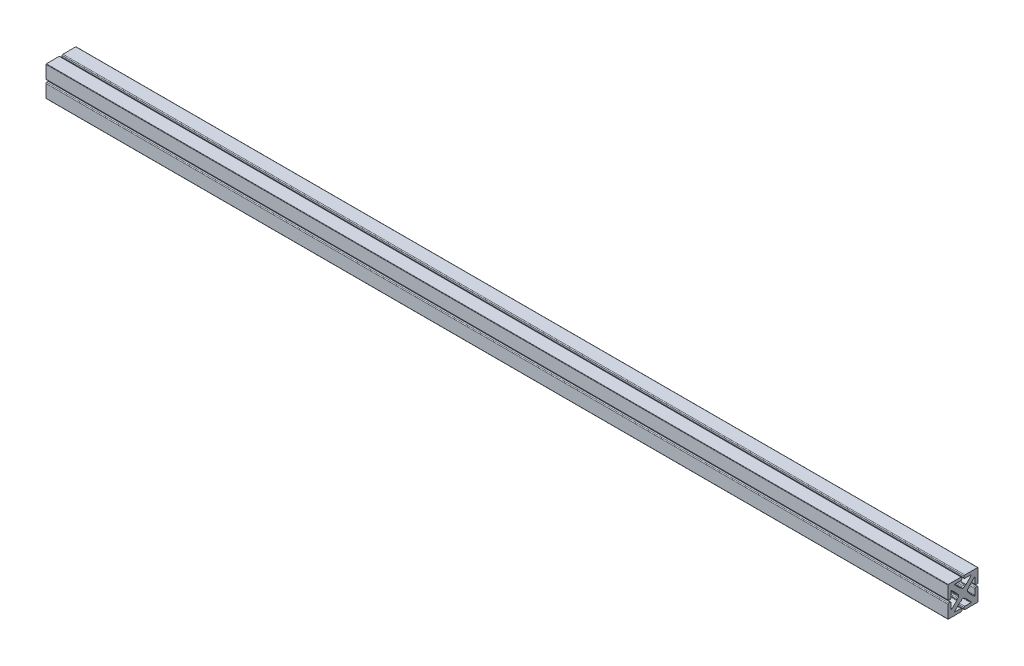
SolidWorks part; units mm, degrees
material "1060 Alloy"
ref_plane "Front Plane" through (0, 0, 0) normal (0, 0, 1) x (1, 0, 0)
ref_plane "Top Plane" through (0, 0, 0) normal (0, 1, 0) x (1, 0, 0)
ref_plane "Right Plane" through (0, 0, 0) normal (1, 0, 0) x (0, 0, -1)
sketch "Sketch1" plane through (0, 0, 0) normal (1, 0, 0) x (0, 0, -1)
  line L0 (0, 0) -> (0, 1.4986) construction
  line L1 (-0.2413, 1.4986) -> (0.2413, 1.4986)
  line L2 (5.0038, 0.635) -> (5.0038, 4.8768)
  line L3 (0.7493, 2.0066) -> (0.8825, 2.0066)
  line L4 (1.0655, 2.0845) -> (2.7141, 3.7982)
  line L5 (2.6226, 4.0132) -> (0.635, 4.0132)
  line L6 (0.381, 4.2672) -> (0.381, 4.7498)
  line L7 (0.635, 5.0038) -> (4.8768, 5.0038)
  line L8 (5.0038, 5.0038) -> (0, 0) construction
  line L9 (0, 0) -> (8.6271, 0) construction
  line L10 (0, 0) -> (0, 5.0038) construction
  line L11 (4.2672, 0.381) -> (4.7498, 0.381)
  line L12 (4.0132, 2.6226) -> (4.0132, 0.635)
  line L13 (2.0845, 1.0655) -> (3.7982, 2.7141)
  line L14 (2.0066, 0.7493) -> (2.0066, 0.8825)
  line L15 (1.4986, -0.2413) -> (1.4986, 0.2413)
  line L16 (0, 0) -> (1.4986, 0) construction
  line L17 (-0.2413, -1.4986) -> (0.2413, -1.4986)
  line L18 (0.7493, -2.0066) -> (0.8825, -2.0066)
  line L19 (1.0655, -2.0845) -> (2.7141, -3.7982)
  line L20 (2.6226, -4.0132) -> (0.635, -4.0132)
  line L21 (0.381, -4.2672) -> (0.381, -4.7498)
  line L22 (0.635, -5.0038) -> (4.8768, -5.0038)
  line L23 (5.0038, -0.635) -> (5.0038, -4.8768)
  line L24 (4.2672, -0.381) -> (4.7498, -0.381)
  line L25 (4.0132, -2.6226) -> (4.0132, -0.635)
  line L26 (2.0845, -1.0655) -> (3.7982, -2.7141)
  line L27 (2.0066, -0.7493) -> (2.0066, -0.8825)
  line L28 (-0.7493, 2.0066) -> (-0.8825, 2.0066)
  line L29 (-1.0655, 2.0845) -> (-2.7141, 3.7982)
  line L30 (-2.6226, 4.0132) -> (-0.635, 4.0132)
  line L31 (-0.381, 4.2672) -> (-0.381, 4.7498)
  line L32 (-0.635, 5.0038) -> (-4.8768, 5.0038)
  line L33 (-5.0038, 0.635) -> (-5.0038, 4.8768)
  line L34 (-4.2672, 0.381) -> (-4.7498, 0.381)
  line L35 (-4.0132, 2.6226) -> (-4.0132, 0.635)
  line L36 (-2.0845, 1.0655) -> (-3.7982, 2.7141)
  line L37 (-2.0066, 0.7493) -> (-2.0066, 0.8825)
  line L38 (-1.4986, -0.2413) -> (-1.4986, 0.2413)
  line L39 (-2.0066, -0.7493) -> (-2.0066, -0.8825)
  line L40 (-2.0845, -1.0655) -> (-3.7982, -2.7141)
  line L41 (-4.0132, -2.6226) -> (-4.0132, -0.635)
  line L42 (-4.2672, -0.381) -> (-4.7498, -0.381)
  line L43 (-5.0038, -0.635) -> (-5.0038, -4.8768)
  line L44 (-0.635, -5.0038) -> (-4.8768, -5.0038)
  line L45 (-0.381, -4.2672) -> (-0.381, -4.7498)
  line L46 (-2.6226, -4.0132) -> (-0.635, -4.0132)
  line L47 (-1.0655, -2.0845) -> (-2.7141, -3.7982)
  line L48 (-0.7493, -2.0066) -> (-0.8825, -2.0066)
  arc A0 (2.7141, 3.7982) -> (2.6226, 4.0132) centre (2.6226, 3.8862) ccw
  arc A1 (0.4953, 1.7526) -> (0.7493, 2.0066) centre (0.7493, 1.7526) cw
  arc A2 (0.8825, 2.0066) -> (1.0655, 2.0845) centre (0.8825, 2.2606) ccw
  arc A3 (0.635, 4.0132) -> (0.381, 4.2672) centre (0.635, 4.2672) cw
  arc A4 (0.381, 4.7498) -> (0.635, 5.0038) centre (0.635, 4.7498) cw
  arc A5 (0.2413, 1.4986) -> (0.4953, 1.7526) centre (0.2413, 1.7526) ccw
  arc A6 (4.7498, 0.381) -> (5.0038, 0.635) centre (4.7498, 0.635) ccw
  arc A7 (4.0132, 0.635) -> (4.2672, 0.381) centre (4.2672, 0.635) ccw
  arc A8 (3.7982, 2.7141) -> (4.0132, 2.6226) centre (3.8862, 2.6226) cw
  arc A9 (2.0066, 0.8825) -> (2.0845, 1.0655) centre (2.2606, 0.8825) cw
  arc A10 (1.7526, 0.4953) -> (2.0066, 0.7493) centre (1.7526, 0.7493) ccw
  arc A11 (1.4986, 0.2413) -> (1.7526, 0.4953) centre (1.7526, 0.2413) cw
  arc A12 (0.2413, -1.4986) -> (0.4953, -1.7526) centre (0.2413, -1.7526) cw
  arc A13 (0.4953, -1.7526) -> (0.7493, -2.0066) centre (0.7493, -1.7526) ccw
  arc A14 (0.8825, -2.0066) -> (1.0655, -2.0845) centre (0.8825, -2.2606) cw
  arc A15 (2.7141, -3.7982) -> (2.6226, -4.0132) centre (2.6226, -3.8862) cw
  arc A16 (0.635, -4.0132) -> (0.381, -4.2672) centre (0.635, -4.2672) ccw
  arc A17 (0.381, -4.7498) -> (0.635, -5.0038) centre (0.635, -4.7498) ccw
  arc A18 (4.7498, -0.381) -> (5.0038, -0.635) centre (4.7498, -0.635) cw
  arc A19 (4.0132, -0.635) -> (4.2672, -0.381) centre (4.2672, -0.635) cw
  arc A20 (3.7982, -2.7141) -> (4.0132, -2.6226) centre (3.8862, -2.6226) ccw
  arc A21 (2.0066, -0.8825) -> (2.0845, -1.0655) centre (2.2606, -0.8825) ccw
  arc A22 (1.7526, -0.4953) -> (2.0066, -0.7493) centre (1.7526, -0.7493) cw
  arc A23 (1.4986, -0.2413) -> (1.7526, -0.4953) centre (1.7526, -0.2413) ccw
  arc A24 (-0.2413, 1.4986) -> (-0.4953, 1.7526) centre (-0.2413, 1.7526) cw
  arc A25 (-0.4953, 1.7526) -> (-0.7493, 2.0066) centre (-0.7493, 1.7526) ccw
  arc A26 (-0.8825, 2.0066) -> (-1.0655, 2.0845) centre (-0.8825, 2.2606) cw
  arc A27 (-2.7141, 3.7982) -> (-2.6226, 4.0132) centre (-2.6226, 3.8862) cw
  arc A28 (-0.635, 4.0132) -> (-0.381, 4.2672) centre (-0.635, 4.2672) ccw
  arc A29 (-0.381, 4.7498) -> (-0.635, 5.0038) centre (-0.635, 4.7498) ccw
  arc A30 (-4.7498, 0.381) -> (-5.0038, 0.635) centre (-4.7498, 0.635) cw
  arc A31 (-4.0132, 0.635) -> (-4.2672, 0.381) centre (-4.2672, 0.635) cw
  arc A32 (-3.7982, 2.7141) -> (-4.0132, 2.6226) centre (-3.8862, 2.6226) ccw
  arc A33 (-2.0066, 0.8825) -> (-2.0845, 1.0655) centre (-2.2606, 0.8825) ccw
  arc A34 (-1.7526, 0.4953) -> (-2.0066, 0.7493) centre (-1.7526, 0.7493) cw
  arc A35 (-1.4986, 0.2413) -> (-1.7526, 0.4953) centre (-1.7526, 0.2413) ccw
  arc A36 (-1.4986, -0.2413) -> (-1.7526, -0.4953) centre (-1.7526, -0.2413) cw
  arc A37 (-1.7526, -0.4953) -> (-2.0066, -0.7493) centre (-1.7526, -0.7493) ccw
  arc A38 (-2.0066, -0.8825) -> (-2.0845, -1.0655) centre (-2.2606, -0.8825) cw
  arc A39 (-3.7982, -2.7141) -> (-4.0132, -2.6226) centre (-3.8862, -2.6226) cw
  arc A40 (-4.0132, -0.635) -> (-4.2672, -0.381) centre (-4.2672, -0.635) ccw
  arc A41 (-4.7498, -0.381) -> (-5.0038, -0.635) centre (-4.7498, -0.635) ccw
  arc A42 (-0.381, -4.7498) -> (-0.635, -5.0038) centre (-0.635, -4.7498) cw
  arc A43 (-0.635, -4.0132) -> (-0.381, -4.2672) centre (-0.635, -4.2672) cw
  arc A44 (-2.7141, -3.7982) -> (-2.6226, -4.0132) centre (-2.6226, -3.8862) ccw
  arc A45 (-0.8825, -2.0066) -> (-1.0655, -2.0845) centre (-0.8825, -2.2606) ccw
  arc A46 (-0.4953, -1.7526) -> (-0.7493, -2.0066) centre (-0.7493, -1.7526) cw
  arc A47 (-0.2413, -1.4986) -> (-0.4953, -1.7526) centre (-0.2413, -1.7526) ccw
  arc A48 (-4.8768, 5.0038) -> (-5.0038, 4.8768) centre (-4.8768, 4.8768) ccw
  arc A49 (-5.0038, -4.8768) -> (-4.8768, -5.0038) centre (-4.8768, -4.8768) ccw
  arc A50 (4.8768, -5.0038) -> (5.0038, -4.8768) centre (4.8768, -4.8768) ccw
  arc A51 (4.8768, 5.0038) -> (5.0038, 4.8768) centre (4.8768, 4.8768) cw
  point P14 (2.921, 4.0132)
  point P19 (0.9906, 2.0066)
  point P150 (0, -1.4986)
  point P152 (-5.0038, 5.0038)
  point P155 (-5.0038, -5.0038)
  point P158 (5.0038, -5.0038)
  dimension "D10" = 0.127
  dimension "D11" = 0.254
  dimension "D2" = 0.127
  dimension "D1" = 10.0076
  dimension "D3" = 2.9972
  dimension "D4" = 0.508
  dimension "D5" = 0.762
  dimension "D6" = 0.9906
  dimension "D7" = 2.54
  dimension "D8" = 1.9812
  dimension "D9" = 0.9906
extrude "Boss-Extrude1" add sketch "Sketch1" along normal blind 2.54 contours L33 A48 L32 A29 L31 A28 L30 A27 L29 A26 L28 A25 A24 L1 A5 A1 L3 A2 L4 A0 L5 A3 L6 A4 L7 A51 L2 A6 L11 A7 L12 A8 L13 A9 L14 A10 A11 L15 A23 A22 L27 A21 L26 A20 L25 A19 L24 A18 L23 A50 L22 A17 L21 A16 L20 A15 L19 A14 L18 A13 A12 L17 A47 A46 L48 A45 L47 A44 L46 A43 L45 A42 L44 A49 L43 A41 L42 A40 L41 A39 L40 A38 L39 A37 A36 L38 A35 A34 L37 A33 L36 A32 L35 A31 L34 A30
scale "Scale1" scale about centroid uniform scaling yes scale factor 8
sketch "Sketch2" plane through (0, 0, 0) normal (1, 0, 0) x (0, 0, -1)
  line L44 (-37.9984, 3.048) -> (-34.1376, 3.048)
  line L45 (-32.1056, 5.08) -> (-32.1056, 20.9808)
  line L46 (-30.3852, 21.7129) -> (-16.676, 8.5244)
  line L47 (-16.0528, 7.06) -> (-16.0528, 5.9944)
  line L48 (-11.9888, 1.9304) -> (-11.9888, -1.9304)
  line L49 (-16.0528, -5.9944) -> (-16.0528, -7.06)
  line L50 (-16.676, -8.5244) -> (-30.3852, -21.7129)
  line L51 (-32.1056, -20.9808) -> (-32.1056, -5.08)
  line L52 (-34.1376, -3.048) -> (-37.9984, -3.048)
  line L53 (-40.0304, -5.08) -> (-40.0304, -39.0144)
  line L54 (-39.0144, -40.0304) -> (-5.08, -40.0304)
  line L55 (-3.048, -37.9984) -> (-3.048, -34.1376)
  line L56 (-5.08, -32.1056) -> (-20.9808, -32.1056)
  line L57 (-21.7129, -30.3852) -> (-8.5244, -16.676)
  line L58 (-7.06, -16.0528) -> (-5.9944, -16.0528)
  line L59 (-1.9304, -11.9888) -> (1.9304, -11.9888)
  line L60 (5.9944, -16.0528) -> (7.06, -16.0528)
  line L61 (8.5244, -16.676) -> (21.7129, -30.3852)
  line L62 (20.9808, -32.1056) -> (5.08, -32.1056)
  line L63 (3.048, -34.1376) -> (3.048, -37.9984)
  line L64 (5.08, -40.0304) -> (39.0144, -40.0304)
  line L65 (40.0304, -39.0144) -> (40.0304, -5.08)
  line L66 (37.9984, -3.048) -> (34.1376, -3.048)
  line L67 (32.1056, -5.08) -> (32.1056, -20.9808)
  line L68 (30.3852, -21.7129) -> (16.676, -8.5244)
  line L69 (16.0528, -7.06) -> (16.0528, -5.9944)
  line L70 (11.9888, -1.9304) -> (11.9888, 1.9304)
  line L71 (16.0528, 5.9944) -> (16.0528, 7.06)
  line L72 (16.676, 8.5244) -> (30.3852, 21.7129)
  line L73 (32.1056, 20.9808) -> (32.1056, 5.08)
  line L74 (34.1376, 3.048) -> (37.9984, 3.048)
  line L75 (40.0304, 5.08) -> (40.0304, 39.0144)
  line L76 (39.0144, 40.0304) -> (5.08, 40.0304)
  line L77 (3.048, 37.9984) -> (3.048, 34.1376)
  line L78 (5.08, 32.1056) -> (20.9808, 32.1056)
  line L79 (21.7129, 30.3852) -> (8.5244, 16.676)
  line L80 (7.06, 16.0528) -> (5.9944, 16.0528)
  line L81 (1.9304, 11.9888) -> (-1.9304, 11.9888)
  line L82 (-5.9944, 16.0528) -> (-7.06, 16.0528)
  line L83 (-8.5244, 16.676) -> (-21.7129, 30.3852)
  line L84 (-20.9808, 32.1056) -> (-5.08, 32.1056)
  line L85 (-3.048, 34.1376) -> (-3.048, 37.9984)
  line L86 (-5.08, 40.0304) -> (-39.0144, 40.0304)
  line L87 (-40.0304, 39.0144) -> (-40.0304, 5.08)
  line L88 (-37.9984, 3.048) -> (-34.1376, 3.048)
  line L89 (-32.1056, 5.08) -> (-32.1056, 20.9808)
  line L90 (-30.3852, 21.7129) -> (-16.676, 8.5244)
  line L91 (-16.0528, 7.06) -> (-16.0528, 5.9944)
  line L92 (-11.9888, 1.9304) -> (-11.9888, -1.9304)
  line L93 (-16.0528, -5.9944) -> (-16.0528, -7.06)
  line L94 (-16.676, -8.5244) -> (-30.3852, -21.7129)
  line L95 (-32.1056, -20.9808) -> (-32.1056, -5.08)
  line L96 (-34.1376, -3.048) -> (-37.9984, -3.048)
  line L97 (-40.0304, -5.08) -> (-40.0304, -39.0144)
  line L98 (-39.0144, -40.0304) -> (-5.08, -40.0304)
  line L99 (-3.048, -37.9984) -> (-3.048, -34.1376)
  line L100 (-5.08, -32.1056) -> (-20.9808, -32.1056)
  line L101 (-21.7129, -30.3852) -> (-8.5244, -16.676)
  line L102 (-7.06, -16.0528) -> (-5.9944, -16.0528)
  line L103 (-1.9304, -11.9888) -> (1.9304, -11.9888)
  line L104 (5.9944, -16.0528) -> (7.06, -16.0528)
  line L105 (8.5244, -16.676) -> (21.7129, -30.3852)
  line L106 (20.9808, -32.1056) -> (5.08, -32.1056)
  line L107 (3.048, -34.1376) -> (3.048, -37.9984)
  line L108 (5.08, -40.0304) -> (39.0144, -40.0304)
  line L109 (40.0304, -39.0144) -> (40.0304, -5.08)
  line L110 (37.9984, -3.048) -> (34.1376, -3.048)
  line L111 (32.1056, -5.08) -> (32.1056, -20.9808)
  line L112 (30.3852, -21.7129) -> (16.676, -8.5244)
  line L113 (16.0528, -7.06) -> (16.0528, -5.9944)
  line L114 (11.9888, -1.9304) -> (11.9888, 1.9304)
  line L115 (16.0528, 5.9944) -> (16.0528, 7.06)
  line L116 (16.676, 8.5244) -> (30.3852, 21.7129)
  line L117 (32.1056, 20.9808) -> (32.1056, 5.08)
  line L118 (34.1376, 3.048) -> (37.9984, 3.048)
  line L119 (40.0304, 5.08) -> (40.0304, 39.0144)
  line L120 (39.0144, 40.0304) -> (5.08, 40.0304)
  line L121 (3.048, 37.9984) -> (3.048, 34.1376)
  line L122 (5.08, 32.1056) -> (20.9808, 32.1056)
  line L123 (21.7129, 30.3852) -> (8.5244, 16.676)
  line L124 (7.06, 16.0528) -> (5.9944, 16.0528)
  line L125 (1.9304, 11.9888) -> (-1.9304, 11.9888)
  line L126 (-5.9944, 16.0528) -> (-7.06, 16.0528)
  line L127 (-8.5244, 16.676) -> (-21.7129, 30.3852)
  line L128 (-20.9808, 32.1056) -> (-5.08, 32.1056)
  line L129 (-3.048, 34.1376) -> (-3.048, 37.9984)
  line L130 (-5.08, 40.0304) -> (-39.0144, 40.0304)
  line L131 (-40.0304, 39.0144) -> (-40.0304, 5.08)
  arc A52 (-40.0304, 5.08) -> (-37.9984, 3.048) centre (-37.9984, 5.08) ccw
  arc A53 (-34.1376, 3.048) -> (-32.1056, 5.08) centre (-34.1376, 5.08) ccw
  arc A54 (-30.3852, 21.7129) -> (-32.1056, 20.9808) centre (-31.0896, 20.9808) ccw
  arc A55 (-16.0528, 7.06) -> (-16.676, 8.5244) centre (-18.0848, 7.06) ccw
  arc A56 (-16.0528, 5.9944) -> (-14.0208, 3.9624) centre (-14.0208, 5.9944) ccw
  arc A57 (-11.9888, 1.9304) -> (-14.0208, 3.9624) centre (-14.0208, 1.9304) ccw
  arc A58 (-14.0208, -3.9624) -> (-11.9888, -1.9304) centre (-14.0208, -1.9304) ccw
  arc A59 (-14.0208, -3.9624) -> (-16.0528, -5.9944) centre (-14.0208, -5.9944) ccw
  arc A60 (-16.676, -8.5244) -> (-16.0528, -7.06) centre (-18.0848, -7.06) ccw
  arc A61 (-32.1056, -20.9808) -> (-30.3852, -21.7129) centre (-31.0896, -20.9808) ccw
  arc A62 (-32.1056, -5.08) -> (-34.1376, -3.048) centre (-34.1376, -5.08) ccw
  arc A63 (-37.9984, -3.048) -> (-40.0304, -5.08) centre (-37.9984, -5.08) ccw
  arc A64 (-40.0304, -39.0144) -> (-39.0144, -40.0304) centre (-39.0144, -39.0144) ccw
  arc A65 (-5.08, -40.0304) -> (-3.048, -37.9984) centre (-5.08, -37.9984) ccw
  arc A66 (-3.048, -34.1376) -> (-5.08, -32.1056) centre (-5.08, -34.1376) ccw
  arc A67 (-21.7129, -30.3852) -> (-20.9808, -32.1056) centre (-20.9808, -31.0896) ccw
  arc A68 (-7.06, -16.0528) -> (-8.5244, -16.676) centre (-7.06, -18.0848) ccw
  arc A69 (-5.9944, -16.0528) -> (-3.9624, -14.0208) centre (-5.9944, -14.0208) ccw
  arc A70 (-1.9304, -11.9888) -> (-3.9624, -14.0208) centre (-1.9304, -14.0208) ccw
  arc A71 (3.9624, -14.0208) -> (1.9304, -11.9888) centre (1.9304, -14.0208) ccw
  arc A72 (3.9624, -14.0208) -> (5.9944, -16.0528) centre (5.9944, -14.0208) ccw
  arc A73 (8.5244, -16.676) -> (7.06, -16.0528) centre (7.06, -18.0848) ccw
  arc A74 (20.9808, -32.1056) -> (21.7129, -30.3852) centre (20.9808, -31.0896) ccw
  arc A75 (5.08, -32.1056) -> (3.048, -34.1376) centre (5.08, -34.1376) ccw
  arc A76 (3.048, -37.9984) -> (5.08, -40.0304) centre (5.08, -37.9984) ccw
  arc A77 (39.0144, -40.0304) -> (40.0304, -39.0144) centre (39.0144, -39.0144) ccw
  arc A78 (40.0304, -5.08) -> (37.9984, -3.048) centre (37.9984, -5.08) ccw
  arc A79 (34.1376, -3.048) -> (32.1056, -5.08) centre (34.1376, -5.08) ccw
  arc A80 (30.3852, -21.7129) -> (32.1056, -20.9808) centre (31.0896, -20.9808) ccw
  arc A81 (16.0528, -7.06) -> (16.676, -8.5244) centre (18.0848, -7.06) ccw
  arc A82 (16.0528, -5.9944) -> (14.0208, -3.9624) centre (14.0208, -5.9944) ccw
  arc A83 (11.9888, -1.9304) -> (14.0208, -3.9624) centre (14.0208, -1.9304) ccw
  arc A84 (14.0208, 3.9624) -> (11.9888, 1.9304) centre (14.0208, 1.9304) ccw
  arc A85 (14.0208, 3.9624) -> (16.0528, 5.9944) centre (14.0208, 5.9944) ccw
  arc A86 (16.676, 8.5244) -> (16.0528, 7.06) centre (18.0848, 7.06) ccw
  arc A87 (32.1056, 20.9808) -> (30.3852, 21.7129) centre (31.0896, 20.9808) ccw
  arc A88 (32.1056, 5.08) -> (34.1376, 3.048) centre (34.1376, 5.08) ccw
  arc A89 (37.9984, 3.048) -> (40.0304, 5.08) centre (37.9984, 5.08) ccw
  arc A90 (40.0304, 39.0144) -> (39.0144, 40.0304) centre (39.0144, 39.0144) ccw
  arc A91 (5.08, 40.0304) -> (3.048, 37.9984) centre (5.08, 37.9984) ccw
  arc A92 (3.048, 34.1376) -> (5.08, 32.1056) centre (5.08, 34.1376) ccw
  arc A93 (21.7129, 30.3852) -> (20.9808, 32.1056) centre (20.9808, 31.0896) ccw
  arc A94 (7.06, 16.0528) -> (8.5244, 16.676) centre (7.06, 18.0848) ccw
  arc A95 (5.9944, 16.0528) -> (3.9624, 14.0208) centre (5.9944, 14.0208) ccw
  arc A96 (1.9304, 11.9888) -> (3.9624, 14.0208) centre (1.9304, 14.0208) ccw
  arc A97 (-3.9624, 14.0208) -> (-1.9304, 11.9888) centre (-1.9304, 14.0208) ccw
  arc A98 (-3.9624, 14.0208) -> (-5.9944, 16.0528) centre (-5.9944, 14.0208) ccw
  arc A99 (-8.5244, 16.676) -> (-7.06, 16.0528) centre (-7.06, 18.0848) ccw
  arc A100 (-20.9808, 32.1056) -> (-21.7129, 30.3852) centre (-20.9808, 31.0896) ccw
  arc A101 (-5.08, 32.1056) -> (-3.048, 34.1376) centre (-5.08, 34.1376) ccw
  arc A102 (-3.048, 37.9984) -> (-5.08, 40.0304) centre (-5.08, 37.9984) ccw
  arc A103 (-39.0144, 40.0304) -> (-40.0304, 39.0144) centre (-39.0144, 39.0144) ccw
  arc A104 (-40.0304, 5.08) -> (-37.9984, 3.048) centre (-37.9984, 5.08) ccw
  arc A105 (-34.1376, 3.048) -> (-32.1056, 5.08) centre (-34.1376, 5.08) ccw
  arc A106 (-30.3852, 21.7129) -> (-32.1056, 20.9808) centre (-31.0896, 20.9808) ccw
  arc A107 (-16.0528, 7.06) -> (-16.676, 8.5244) centre (-18.0848, 7.06) ccw
  arc A108 (-16.0528, 5.9944) -> (-14.0208, 3.9624) centre (-14.0208, 5.9944) ccw
  arc A109 (-11.9888, 1.9304) -> (-14.0208, 3.9624) centre (-14.0208, 1.9304) ccw
  arc A110 (-14.0208, -3.9624) -> (-11.9888, -1.9304) centre (-14.0208, -1.9304) ccw
  arc A111 (-14.0208, -3.9624) -> (-16.0528, -5.9944) centre (-14.0208, -5.9944) ccw
  arc A112 (-16.676, -8.5244) -> (-16.0528, -7.06) centre (-18.0848, -7.06) ccw
  arc A113 (-32.1056, -20.9808) -> (-30.3852, -21.7129) centre (-31.0896, -20.9808) ccw
  arc A114 (-32.1056, -5.08) -> (-34.1376, -3.048) centre (-34.1376, -5.08) ccw
  arc A115 (-37.9984, -3.048) -> (-40.0304, -5.08) centre (-37.9984, -5.08) ccw
  arc A116 (-40.0304, -39.0144) -> (-39.0144, -40.0304) centre (-39.0144, -39.0144) ccw
  arc A117 (-5.08, -40.0304) -> (-3.048, -37.9984) centre (-5.08, -37.9984) ccw
  arc A118 (-3.048, -34.1376) -> (-5.08, -32.1056) centre (-5.08, -34.1376) ccw
  arc A119 (-21.7129, -30.3852) -> (-20.9808, -32.1056) centre (-20.9808, -31.0896) ccw
  arc A120 (-7.06, -16.0528) -> (-8.5244, -16.676) centre (-7.06, -18.0848) ccw
  arc A121 (-5.9944, -16.0528) -> (-3.9624, -14.0208) centre (-5.9944, -14.0208) ccw
  arc A122 (-1.9304, -11.9888) -> (-3.9624, -14.0208) centre (-1.9304, -14.0208) ccw
  arc A123 (3.9624, -14.0208) -> (1.9304, -11.9888) centre (1.9304, -14.0208) ccw
  arc A124 (3.9624, -14.0208) -> (5.9944, -16.0528) centre (5.9944, -14.0208) ccw
  arc A125 (8.5244, -16.676) -> (7.06, -16.0528) centre (7.06, -18.0848) ccw
  arc A126 (20.9808, -32.1056) -> (21.7129, -30.3852) centre (20.9808, -31.0896) ccw
  arc A127 (5.08, -32.1056) -> (3.048, -34.1376) centre (5.08, -34.1376) ccw
  arc A128 (3.048, -37.9984) -> (5.08, -40.0304) centre (5.08, -37.9984) ccw
  arc A129 (39.0144, -40.0304) -> (40.0304, -39.0144) centre (39.0144, -39.0144) ccw
  arc A130 (40.0304, -5.08) -> (37.9984, -3.048) centre (37.9984, -5.08) ccw
  arc A131 (34.1376, -3.048) -> (32.1056, -5.08) centre (34.1376, -5.08) ccw
  arc A132 (30.3852, -21.7129) -> (32.1056, -20.9808) centre (31.0896, -20.9808) ccw
  arc A133 (16.0528, -7.06) -> (16.676, -8.5244) centre (18.0848, -7.06) ccw
  arc A134 (16.0528, -5.9944) -> (14.0208, -3.9624) centre (14.0208, -5.9944) ccw
  arc A135 (11.9888, -1.9304) -> (14.0208, -3.9624) centre (14.0208, -1.9304) ccw
  arc A136 (14.0208, 3.9624) -> (11.9888, 1.9304) centre (14.0208, 1.9304) ccw
  arc A137 (14.0208, 3.9624) -> (16.0528, 5.9944) centre (14.0208, 5.9944) ccw
  arc A138 (16.676, 8.5244) -> (16.0528, 7.06) centre (18.0848, 7.06) ccw
  arc A139 (32.1056, 20.9808) -> (30.3852, 21.7129) centre (31.0896, 20.9808) ccw
  arc A140 (32.1056, 5.08) -> (34.1376, 3.048) centre (34.1376, 5.08) ccw
  arc A141 (37.9984, 3.048) -> (40.0304, 5.08) centre (37.9984, 5.08) ccw
  arc A142 (40.0304, 39.0144) -> (39.0144, 40.0304) centre (39.0144, 39.0144) ccw
  arc A143 (5.08, 40.0304) -> (3.048, 37.9984) centre (5.08, 37.9984) ccw
  arc A144 (3.048, 34.1376) -> (5.08, 32.1056) centre (5.08, 34.1376) ccw
  arc A145 (21.7129, 30.3852) -> (20.9808, 32.1056) centre (20.9808, 31.0896) ccw
  arc A146 (7.06, 16.0528) -> (8.5244, 16.676) centre (7.06, 18.0848) ccw
  arc A147 (5.9944, 16.0528) -> (3.9624, 14.0208) centre (5.9944, 14.0208) ccw
  arc A148 (1.9304, 11.9888) -> (3.9624, 14.0208) centre (1.9304, 14.0208) ccw
  arc A149 (-3.9624, 14.0208) -> (-1.9304, 11.9888) centre (-1.9304, 14.0208) ccw
  arc A150 (-3.9624, 14.0208) -> (-5.9944, 16.0528) centre (-5.9944, 14.0208) ccw
  arc A151 (-8.5244, 16.676) -> (-7.06, 16.0528) centre (-7.06, 18.0848) ccw
  arc A152 (-20.9808, 32.1056) -> (-21.7129, 30.3852) centre (-20.9808, 31.0896) ccw
  arc A153 (-5.08, 32.1056) -> (-3.048, 34.1376) centre (-5.08, 34.1376) ccw
  arc A154 (-3.048, 37.9984) -> (-5.08, 40.0304) centre (-5.08, 37.9984) ccw
  arc A155 (-39.0144, 40.0304) -> (-40.0304, 39.0144) centre (-39.0144, 39.0144) ccw
  dimension "D1" = 0
extrude "Boss-Extrude2" add sketch "Sketch2" along normal mid plane 2400
ref_point "Point1"
ref_point "Point2"
